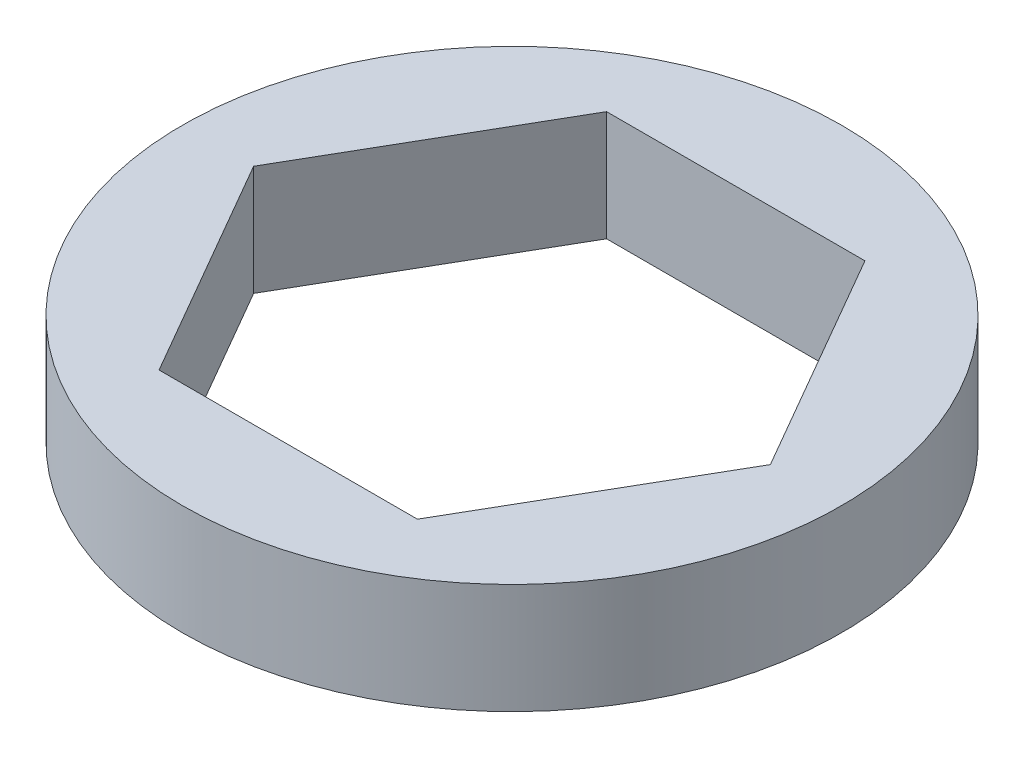
SolidWorks part; units mm, degrees
ref_plane "Front" through (0, 0, 0) normal (0, 0, 1) x (1, 0, 0)
ref_plane "Top" through (0, 0, 0) normal (0, 1, 0) x (1, 0, 0)
ref_plane "Right" through (0, 0, 0) normal (1, 0, 0) x (0, 0, -1)
sketch "Sketch1" plane through (0, 0, 0) normal (0, 1, 0) x (1, 0, 0)
  line L1 (7.4478, 0) -> (3.7239, 6.45)
  line L2 (3.7239, 6.45) -> (-3.7239, 6.45)
  line L3 (-3.7239, 6.45) -> (-7.4478, 0)
  line L4 (-7.4478, 0) -> (-3.7239, -6.45)
  line L5 (-3.7239, -6.45) -> (3.7239, -6.45)
  line L6 (3.7239, -6.45) -> (7.4478, 0)
  circle A0 centre (0, 0) radius 9.5
  circle A1 centre (0, 0) radius 6.45 construction
  dimension "D1" = 12.9
  dimension "D2" = 19
extrude "Boss-Extrude1" add sketch "Sketch1" along normal blind 3.175
